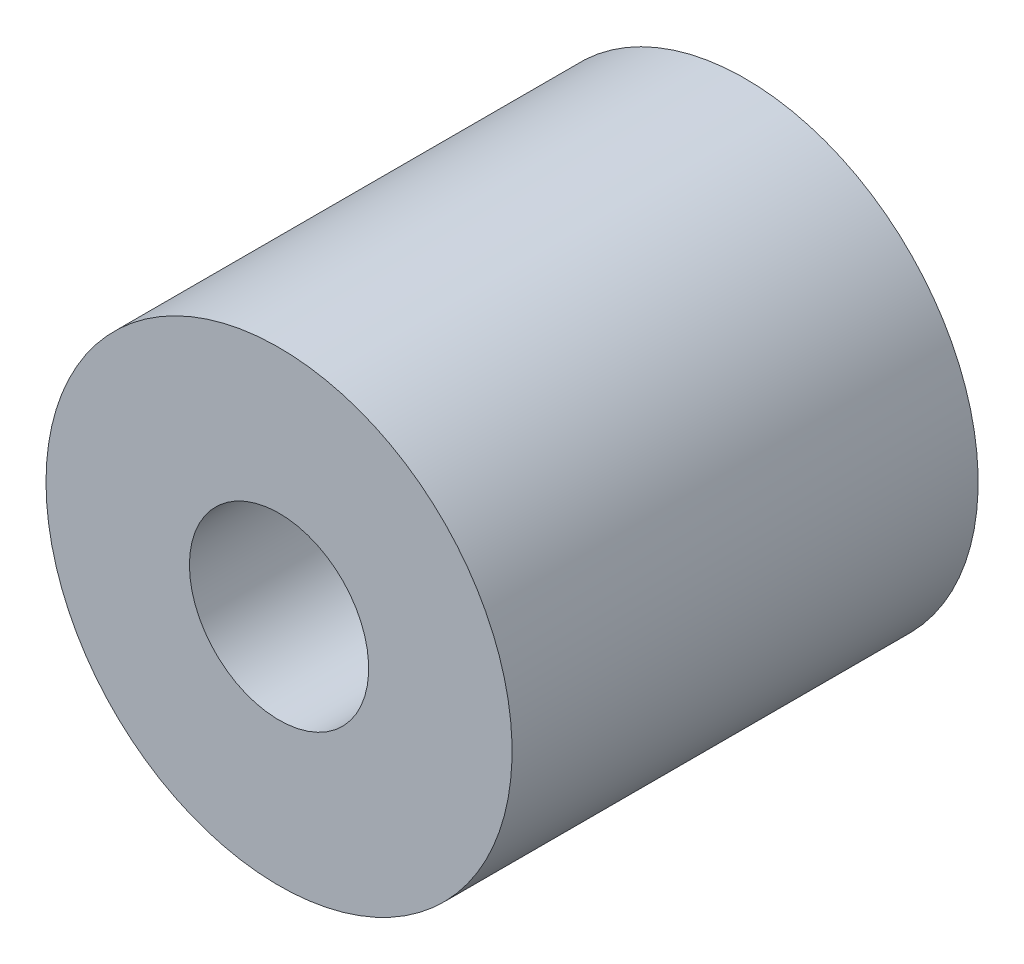
SolidWorks part; units mm, degrees
ref_plane "前视基准面" through (0, 0, 0) normal (0, 0, 1) x (1, 0, 0)
ref_plane "上视基准面" through (0, 0, 0) normal (0, 1, 0) x (1, 0, 0)
ref_plane "右视基准面" through (0, 0, 0) normal (1, 0, 0) x (0, 0, -1)
sketch "草图1" plane through (0, 0, 0) normal (0, 0, 1) x (1, 0, 0)
  circle A0 centre (0, 0) radius 13
  circle A1 centre (0, 0) radius 5
  dimension "D1" = 26
  dimension "D2" = 10
extrude "凸台-拉伸1" add sketch "草图1" along normal blind 26
